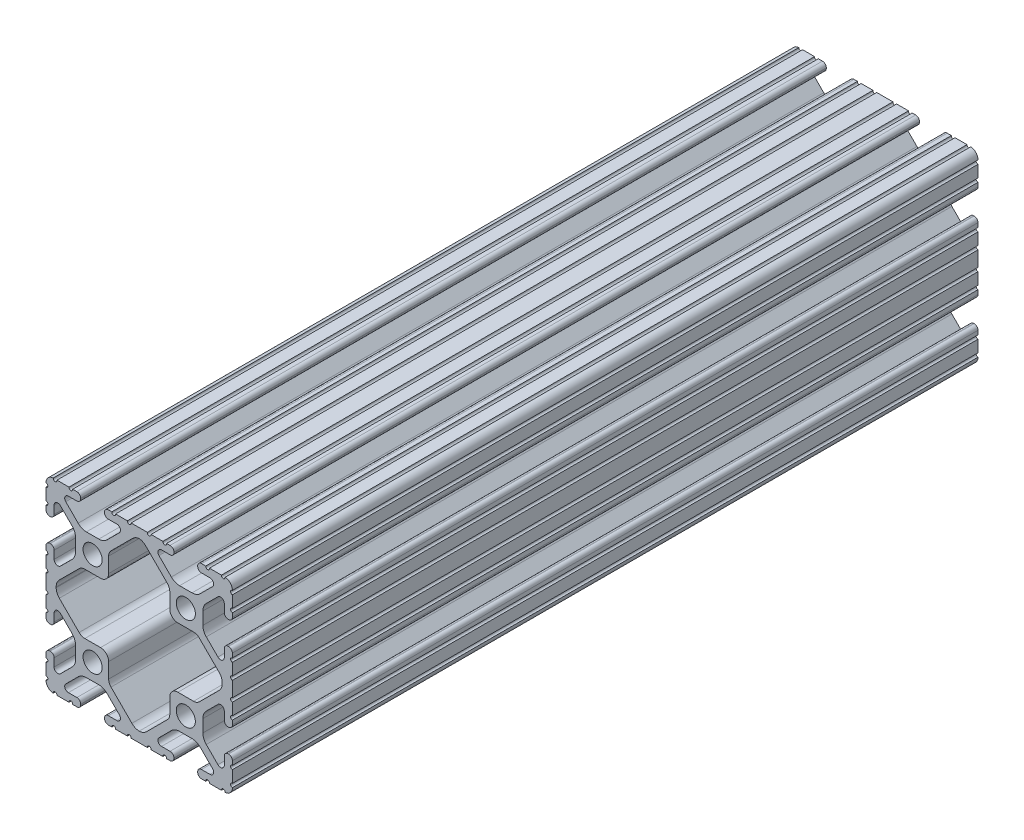
SolidWorks part; units mm, degrees
material "6061-T6 (SS)"
ref_plane "Front Plane" through (0, 0, 0) normal (0, 0, 1) x (1, 0, 0)
ref_plane "Top Plane" through (0, 0, 0) normal (0, 1, 0) x (1, 0, 0)
ref_plane "Right Plane" through (0, 0, 0) normal (1, 0, 0) x (0, 0, -1)
sketch "Sketch1" plane through (0, 0, 0) normal (0, 0, 1) x (1, 0, 0)
  line L0 (-7.684, -16.0797) -> (-1.9878, -21.7759)
  line L1 (-8.3312, -10.3886) -> (-8.3312, -14.5171)
  line L2 (-14.8165, -8.1788) -> (-10.541, -8.1788)
  line L3 (-21.7734, -2.1502) -> (-16.3772, -7.5334)
  line L4 (-22.6314, 0.0822) -> (-22.6314, -0.0822)
  line L5 (-16.3772, 7.5334) -> (-21.7734, 2.1502)
  line L6 (-10.541, 8.1788) -> (-14.8165, 8.1788)
  line L7 (-8.3312, 14.5171) -> (-8.3312, 10.3886)
  line L8 (-1.7956, 21.9681) -> (-7.684, 16.0797)
  line L9 (7.684, 16.0797) -> (1.7956, 21.9681)
  line L10 (8.3312, 10.389) -> (8.3312, 14.5171)
  line L11 (14.8161, 8.1792) -> (10.541, 8.1792)
  line L12 (21.7734, 2.1502) -> (16.3768, 7.5339)
  line L13 (22.6314, -0.0822) -> (22.6314, 0.0822)
  line L14 (16.3772, -7.5334) -> (21.7734, -2.1502)
  line L15 (10.541, -8.1788) -> (14.8165, -8.1788)
  line L16 (8.3312, -14.5171) -> (8.3312, -10.3886)
  line L17 (1.9878, -21.7759) -> (7.684, -16.0797)
  line L18 (7.4579, -25.4) -> (8.4051, -25.4)
  line L19 (9.4615, -24.3587) -> (9.4615, -24.2315)
  line L20 (8.4051, -23.1902) -> (6.0878, -23.1902)
  line L21 (5.388, -21.5008) -> (8.763, -18.1257)
  line L22 (11.0081, -17.1958) -> (14.3919, -17.1958)
  line L23 (16.637, -18.1257) -> (20.012, -21.5008)
  line L24 (19.2977, -23.1901) -> (16.9799, -23.1901)
  line L25 (15.9385, -24.2315) -> (15.9385, -24.3587)
  line L26 (16.9949, -25.4) -> (18.134, -25.4)
  line L27 (19.1384, -25.4) -> (22.4132, -25.4)
  line L28 (23.4176, -25.4) -> (23.4501, -25.4)
  line L29 (25.4, -23.2977) -> (25.4, -23.2686)
  line L30 (25.4, -22.2526) -> (25.4, -19.0252)
  line L31 (25.4, -18.0092) -> (25.4, -16.916)
  line L32 (24.3586, -15.8746) -> (24.2316, -15.8746)
  line L33 (23.1902, -16.916) -> (23.1902, -19.101)
  line L34 (21.4558, -19.8194) -> (18.2781, -16.6418)
  line L35 (17.3482, -14.3967) -> (17.3482, -11.0035)
  line L36 (18.2808, -8.7557) -> (21.4566, -5.5875)
  line L37 (23.1902, -6.3068) -> (23.1902, -8.484)
  line L38 (24.2316, -9.5254) -> (24.3586, -9.5254)
  line L39 (25.4, -8.484) -> (25.4, -7.3277)
  line L40 (25.4, -6.3117) -> (25.4, -3.0843)
  line L41 (25.4, -2.0683) -> (25.4, 2.0683)
  line L42 (25.4, 3.0843) -> (25.4, 6.3117)
  line L43 (25.4, 7.3277) -> (25.4, 8.484)
  line L44 (24.3586, 9.5254) -> (24.2316, 9.5254)
  line L45 (23.1902, 8.484) -> (23.1902, 6.3068)
  line L46 (21.4566, 5.5875) -> (18.2808, 8.7557)
  line L47 (17.3482, 11.0035) -> (17.3482, 14.3967)
  line L48 (18.2781, 16.6418) -> (21.4558, 19.8194)
  line L49 (23.1902, 19.101) -> (23.1902, 16.916)
  line L50 (24.2316, 15.8746) -> (24.3586, 15.8746)
  line L51 (25.4, 16.916) -> (25.4, 18.0092)
  line L52 (25.4, 19.0252) -> (25.4, 22.2526)
  line L53 (25.4, 23.2686) -> (25.4, 23.2977)
  line L54 (23.4501, 25.4) -> (23.4176, 25.4)
  line L55 (22.4132, 25.4) -> (19.1384, 25.4)
  line L56 (18.134, 25.4) -> (16.9949, 25.4)
  line L57 (15.9385, 24.3587) -> (15.9385, 24.2315)
  line L58 (16.9799, 23.1901) -> (19.2977, 23.1901)
  line L59 (20.012, 21.5008) -> (16.637, 18.1257)
  line L60 (14.3919, 17.1958) -> (11.0081, 17.1958)
  line L61 (8.763, 18.1257) -> (5.388, 21.5008)
  line L62 (6.0878, 23.1902) -> (8.4051, 23.1902)
  line L63 (9.4615, 24.2315) -> (9.4615, 24.3587)
  line L64 (8.4051, 25.4) -> (7.4579, 25.4)
  line L65 (6.4535, 25.4) -> (3.2145, 25.4)
  line L66 (2.2101, 25.4) -> (-2.2101, 25.4)
  line L67 (-3.2145, 25.4) -> (-6.4535, 25.4)
  line L68 (-7.4579, 25.4) -> (-8.4051, 25.4)
  line L69 (-9.4615, 24.3587) -> (-9.4615, 24.2315)
  line L70 (-8.4051, 23.1902) -> (-6.0878, 23.1902)
  line L71 (-5.388, 21.5008) -> (-8.763, 18.1257)
  line L72 (-11.0081, 17.1958) -> (-14.3919, 17.1958)
  line L73 (-16.637, 18.1257) -> (-20.012, 21.5008)
  line L74 (-19.2977, 23.1901) -> (-16.9799, 23.1901)
  line L75 (-15.9385, 24.2315) -> (-15.9385, 24.3587)
  line L76 (-16.9949, 25.4) -> (-18.134, 25.4)
  line L77 (-19.1384, 25.4) -> (-22.4132, 25.4)
  line L78 (-23.4176, 25.4) -> (-23.4501, 25.4)
  line L79 (-25.4, 23.2977) -> (-25.4, 23.2686)
  line L80 (-25.4, 22.2526) -> (-25.4, 19.0252)
  line L81 (-25.4, 18.0092) -> (-25.4, 16.916)
  line L82 (-24.3586, 15.8746) -> (-24.2316, 15.8746)
  line L83 (-23.1902, 16.916) -> (-23.1902, 19.101)
  line L84 (-21.4558, 19.8194) -> (-18.2781, 16.6418)
  line L85 (-17.3482, 14.3967) -> (-17.3482, 11.0035)
  line L86 (-18.2808, 8.7557) -> (-21.4566, 5.5875)
  line L87 (-23.1902, 6.3068) -> (-23.1902, 8.484)
  line L88 (-24.2316, 9.5254) -> (-24.3586, 9.5254)
  line L89 (-25.4, 8.484) -> (-25.4, 7.3277)
  line L90 (-25.4, 6.3117) -> (-25.4, 3.0843)
  line L91 (-25.4, 2.0683) -> (-25.4, -2.0683)
  line L92 (-25.4, -3.0843) -> (-25.4, -6.3117)
  line L93 (-25.4, -7.3277) -> (-25.4, -8.484)
  line L94 (-24.3586, -9.5254) -> (-24.2316, -9.5254)
  line L95 (-23.1902, -8.484) -> (-23.1902, -6.3068)
  line L96 (-21.4566, -5.5875) -> (-18.2808, -8.7557)
  line L97 (-17.3482, -11.0035) -> (-17.3482, -14.3967)
  line L98 (-18.2781, -16.6418) -> (-21.4558, -19.8194)
  line L99 (-23.1902, -19.101) -> (-23.1902, -16.916)
  line L100 (-24.2316, -15.8746) -> (-24.3586, -15.8746)
  line L101 (-25.4, -16.916) -> (-25.4, -18.0092)
  line L102 (-25.4, -19.0252) -> (-25.4, -22.2526)
  line L103 (-25.4, -23.2686) -> (-25.4, -23.2977)
  line L104 (-23.4501, -25.4) -> (-23.4176, -25.4)
  line L105 (-22.4132, -25.4) -> (-19.1384, -25.4)
  line L106 (-18.134, -25.4) -> (-16.9949, -25.4)
  line L107 (-15.9385, -24.3587) -> (-15.9385, -24.2315)
  line L108 (-16.9799, -23.1901) -> (-19.2977, -23.1901)
  line L109 (-20.012, -21.5008) -> (-16.637, -18.1257)
  line L110 (-14.3919, -17.1958) -> (-11.0081, -17.1958)
  line L111 (-8.763, -18.1257) -> (-5.388, -21.5008)
  line L112 (-6.0878, -23.1902) -> (-8.4051, -23.1902)
  line L113 (-9.4615, -24.2315) -> (-9.4615, -24.3587)
  line L114 (-8.4051, -25.4) -> (-7.4579, -25.4)
  line L115 (-6.4535, -25.4) -> (-3.2145, -25.4)
  line L116 (-2.2101, -25.4) -> (2.2101, -25.4)
  line L117 (3.2145, -25.4) -> (6.4535, -25.4)
  circle A0 centre (-12.7, 12.7) radius 2.6035
  circle A1 centre (12.7, 12.7) radius 2.6035
  circle A2 centre (12.7, -12.7) radius 2.6035
  circle A3 centre (-12.7, -12.7) radius 2.6035
  arc A4 (-1.9878, -21.7759) -> (0, -22.6304) centre (0.0777, -19.7104) ccw
  arc A5 (-8.3312, -14.5171) -> (-7.684, -16.0797) centre (-6.1214, -14.5171) ccw
  arc A6 (-8.3312, -10.3886) -> (-10.541, -8.1788) centre (-10.541, -10.3886) ccw
  arc A7 (-16.3772, -7.5334) -> (-14.8165, -8.1788) centre (-14.8165, -5.969) ccw
  arc A8 (-22.6314, -0.0822) -> (-21.7734, -2.1502) centre (-19.7104, -0.0822) ccw
  arc A9 (-21.7734, 2.1502) -> (-22.6314, 0.0822) centre (-19.7104, 0.0822) ccw
  arc A10 (-14.8165, 8.1788) -> (-16.3772, 7.5334) centre (-14.8165, 5.969) ccw
  arc A11 (-10.541, 8.1788) -> (-8.3312, 10.3886) centre (-10.541, 10.3886) ccw
  arc A12 (-7.684, 16.0797) -> (-8.3312, 14.5171) centre (-6.1214, 14.5171) ccw
  arc A13 (0, 22.8111) -> (-1.7956, 21.9681) centre (0.2699, 19.9026) ccw
  arc A14 (1.7956, 21.9681) -> (0, 22.8111) centre (-0.2699, 19.9026) ccw
  arc A15 (8.3312, 14.5171) -> (7.684, 16.0797) centre (6.1214, 14.5171) ccw
  arc A16 (8.3312, 10.389) -> (10.541, 8.1792) centre (10.541, 10.389) ccw
  arc A17 (16.3768, 7.5339) -> (14.8161, 8.1792) centre (14.8161, 5.9694) ccw
  arc A18 (22.6314, 0.0822) -> (21.7734, 2.1502) centre (19.7104, 0.0822) ccw
  arc A19 (21.7734, -2.1502) -> (22.6314, -0.0822) centre (19.7104, -0.0822) ccw
  arc A20 (14.8165, -8.1788) -> (16.3772, -7.5334) centre (14.8165, -5.969) ccw
  arc A21 (10.541, -8.1788) -> (8.3312, -10.3886) centre (10.541, -10.3886) ccw
  arc A22 (7.684, -16.0797) -> (8.3312, -14.5171) centre (6.1214, -14.5171) ccw
  arc A23 (0, -22.6304) -> (1.9878, -21.7759) centre (-0.0777, -19.7104) ccw
  arc A24 (7.4579, -25.4) -> (6.4535, -25.4) centre (6.9557, -25.3234) ccw
  arc A25 (8.4051, -25.4) -> (9.4615, -24.3587) centre (8.4201, -24.3587) ccw
  arc A26 (9.4615, -24.2315) -> (8.4051, -23.1902) centre (8.4201, -24.2315) ccw
  arc A27 (5.388, -21.5008) -> (6.0878, -23.1902) centre (6.0878, -22.2006) ccw
  arc A28 (11.0081, -17.1958) -> (8.763, -18.1257) centre (11.0081, -20.3708) ccw
  arc A29 (16.637, -18.1257) -> (14.3919, -17.1958) centre (14.3919, -20.3708) ccw
  arc A30 (19.2977, -23.1901) -> (20.012, -21.5008) centre (19.3122, -22.2006) ccw
  arc A31 (16.9799, -23.1901) -> (15.9385, -24.2315) centre (16.9799, -24.2315) ccw
  arc A32 (15.9385, -24.3587) -> (16.9949, -25.4) centre (16.9799, -24.3587) ccw
  arc A33 (19.1384, -25.4) -> (18.134, -25.4) centre (18.6362, -25.3234) ccw
  arc A34 (23.4176, -25.4) -> (22.4132, -25.4) centre (22.9154, -25.3234) ccw
  arc A35 (23.4501, -25.4) -> (25.4, -23.2977) centre (23.2918, -23.2977) ccw
  arc A36 (25.4, -22.2526) -> (25.4, -23.2686) centre (25.4, -22.7606) ccw
  arc A37 (25.4, -18.0092) -> (25.4, -19.0252) centre (25.4, -18.5172) ccw
  arc A38 (25.4, -16.916) -> (24.3586, -15.8746) centre (24.3586, -16.916) ccw
  arc A39 (24.2316, -15.8746) -> (23.1902, -16.916) centre (24.2316, -16.916) ccw
  arc A40 (21.4558, -19.8194) -> (23.1902, -19.101) centre (22.1742, -19.101) ccw
  arc A41 (17.3482, -14.3967) -> (18.2781, -16.6418) centre (20.5232, -14.3967) ccw
  arc A42 (18.2808, -8.7557) -> (17.3482, -11.0035) centre (20.5232, -11.0035) ccw
  arc A43 (23.1902, -6.3068) -> (21.4566, -5.5875) centre (22.1742, -6.3068) ccw
  arc A44 (23.1902, -8.484) -> (24.2316, -9.5254) centre (24.2316, -8.484) ccw
  arc A45 (24.3586, -9.5254) -> (25.4, -8.484) centre (24.3586, -8.484) ccw
  arc A46 (25.4, -6.3117) -> (25.4, -7.3277) centre (25.4, -6.8197) ccw
  arc A47 (25.4, -2.0683) -> (25.4, -3.0843) centre (25.4, -2.5763) ccw
  arc A48 (25.4, 3.0843) -> (25.4, 2.0683) centre (25.4, 2.5763) ccw
  arc A49 (25.4, 7.3277) -> (25.4, 6.3117) centre (25.4, 6.8197) ccw
  arc A50 (25.4, 8.484) -> (24.3586, 9.5254) centre (24.3586, 8.484) ccw
  arc A51 (24.2316, 9.5254) -> (23.1902, 8.484) centre (24.2316, 8.484) ccw
  arc A52 (21.4566, 5.5875) -> (23.1902, 6.3068) centre (22.1742, 6.3068) ccw
  arc A53 (17.3482, 11.0035) -> (18.2808, 8.7557) centre (20.5232, 11.0035) ccw
  arc A54 (18.2781, 16.6418) -> (17.3482, 14.3967) centre (20.5232, 14.3967) ccw
  arc A55 (23.1902, 19.101) -> (21.4558, 19.8194) centre (22.1742, 19.101) ccw
  arc A56 (23.1902, 16.916) -> (24.2316, 15.8746) centre (24.2316, 16.916) ccw
  arc A57 (24.3586, 15.8746) -> (25.4, 16.916) centre (24.3586, 16.916) ccw
  arc A58 (25.4, 19.0252) -> (25.4, 18.0092) centre (25.4, 18.5172) ccw
  arc A59 (25.4, 23.2686) -> (25.4, 22.2526) centre (25.4, 22.7606) ccw
  arc A60 (25.4, 23.2977) -> (23.4501, 25.4) centre (23.2918, 23.2977) ccw
  arc A61 (22.4132, 25.4) -> (23.4176, 25.4) centre (22.9154, 25.3234) ccw
  arc A62 (18.134, 25.4) -> (19.1384, 25.4) centre (18.6362, 25.3234) ccw
  arc A63 (16.9949, 25.4) -> (15.9385, 24.3587) centre (16.9799, 24.3587) ccw
  arc A64 (15.9385, 24.2315) -> (16.9799, 23.1901) centre (16.9799, 24.2315) ccw
  arc A65 (20.012, 21.5008) -> (19.2977, 23.1901) centre (19.3122, 22.2006) ccw
  arc A66 (14.3919, 17.1958) -> (16.637, 18.1257) centre (14.3919, 20.3708) ccw
  arc A67 (8.763, 18.1257) -> (11.0081, 17.1958) centre (11.0081, 20.3708) ccw
  arc A68 (6.0878, 23.1902) -> (5.388, 21.5008) centre (6.0878, 22.2006) ccw
  arc A69 (8.4051, 23.1902) -> (9.4615, 24.2315) centre (8.4201, 24.2315) ccw
  arc A70 (9.4615, 24.3587) -> (8.4051, 25.4) centre (8.4201, 24.3587) ccw
  arc A71 (6.4535, 25.4) -> (7.4579, 25.4) centre (6.9557, 25.3234) ccw
  arc A72 (2.2101, 25.4) -> (3.2145, 25.4) centre (2.7123, 25.3234) ccw
  arc A73 (-3.2145, 25.4) -> (-2.2101, 25.4) centre (-2.7123, 25.3234) ccw
  arc A74 (-7.4579, 25.4) -> (-6.4535, 25.4) centre (-6.9557, 25.3234) ccw
  arc A75 (-8.4051, 25.4) -> (-9.4615, 24.3587) centre (-8.4201, 24.3587) ccw
  arc A76 (-9.4615, 24.2315) -> (-8.4051, 23.1902) centre (-8.4201, 24.2315) ccw
  arc A77 (-5.388, 21.5008) -> (-6.0878, 23.1902) centre (-6.0878, 22.2006) ccw
  arc A78 (-11.0081, 17.1958) -> (-8.763, 18.1257) centre (-11.0081, 20.3708) ccw
  arc A79 (-16.637, 18.1257) -> (-14.3919, 17.1958) centre (-14.3919, 20.3708) ccw
  arc A80 (-19.2977, 23.1901) -> (-20.012, 21.5008) centre (-19.3122, 22.2006) ccw
  arc A81 (-16.9799, 23.1901) -> (-15.9385, 24.2315) centre (-16.9799, 24.2315) ccw
  arc A82 (-15.9385, 24.3587) -> (-16.9949, 25.4) centre (-16.9799, 24.3587) ccw
  arc A83 (-19.1384, 25.4) -> (-18.134, 25.4) centre (-18.6362, 25.3234) ccw
  arc A84 (-23.4176, 25.4) -> (-22.4132, 25.4) centre (-22.9154, 25.3234) ccw
  arc A85 (-23.4501, 25.4) -> (-25.4, 23.2977) centre (-23.2918, 23.2977) ccw
  arc A86 (-25.4, 22.2526) -> (-25.4, 23.2686) centre (-25.4, 22.7606) ccw
  arc A87 (-25.4, 18.0092) -> (-25.4, 19.0252) centre (-25.4, 18.5172) ccw
  arc A88 (-25.4, 16.916) -> (-24.3586, 15.8746) centre (-24.3586, 16.916) ccw
  arc A89 (-24.2316, 15.8746) -> (-23.1902, 16.916) centre (-24.2316, 16.916) ccw
  arc A90 (-21.4558, 19.8194) -> (-23.1902, 19.101) centre (-22.1742, 19.101) ccw
  arc A91 (-17.3482, 14.3967) -> (-18.2781, 16.6418) centre (-20.5232, 14.3967) ccw
  arc A92 (-18.2808, 8.7557) -> (-17.3482, 11.0035) centre (-20.5232, 11.0035) ccw
  arc A93 (-23.1902, 6.3068) -> (-21.4566, 5.5875) centre (-22.1742, 6.3068) ccw
  arc A94 (-23.1902, 8.484) -> (-24.2316, 9.5254) centre (-24.2316, 8.484) ccw
  arc A95 (-24.3586, 9.5254) -> (-25.4, 8.484) centre (-24.3586, 8.484) ccw
  arc A96 (-25.4, 6.3117) -> (-25.4, 7.3277) centre (-25.4, 6.8197) ccw
  arc A97 (-25.4, 2.0683) -> (-25.4, 3.0843) centre (-25.4, 2.5763) ccw
  arc A98 (-25.4, -3.0843) -> (-25.4, -2.0683) centre (-25.4, -2.5763) ccw
  arc A99 (-25.4, -7.3277) -> (-25.4, -6.3117) centre (-25.4, -6.8197) ccw
  arc A100 (-25.4, -8.484) -> (-24.3586, -9.5254) centre (-24.3586, -8.484) ccw
  arc A101 (-24.2316, -9.5254) -> (-23.1902, -8.484) centre (-24.2316, -8.484) ccw
  arc A102 (-21.4566, -5.5875) -> (-23.1902, -6.3068) centre (-22.1742, -6.3068) ccw
  arc A103 (-17.3482, -11.0035) -> (-18.2808, -8.7557) centre (-20.5232, -11.0035) ccw
  arc A104 (-18.2781, -16.6418) -> (-17.3482, -14.3967) centre (-20.5232, -14.3967) ccw
  arc A105 (-23.1902, -19.101) -> (-21.4558, -19.8194) centre (-22.1742, -19.101) ccw
  arc A106 (-23.1902, -16.916) -> (-24.2316, -15.8746) centre (-24.2316, -16.916) ccw
  arc A107 (-24.3586, -15.8746) -> (-25.4, -16.916) centre (-24.3586, -16.916) ccw
  arc A108 (-25.4, -19.0252) -> (-25.4, -18.0092) centre (-25.4, -18.5172) ccw
  arc A109 (-25.4, -23.2686) -> (-25.4, -22.2526) centre (-25.4, -22.7606) ccw
  arc A110 (-25.4, -23.2977) -> (-23.4501, -25.4) centre (-23.2918, -23.2977) ccw
  arc A111 (-22.4132, -25.4) -> (-23.4176, -25.4) centre (-22.9154, -25.3234) ccw
  arc A112 (-18.134, -25.4) -> (-19.1384, -25.4) centre (-18.6362, -25.3234) ccw
  arc A113 (-16.9949, -25.4) -> (-15.9385, -24.3587) centre (-16.9799, -24.3587) ccw
  arc A114 (-15.9385, -24.2315) -> (-16.9799, -23.1901) centre (-16.9799, -24.2315) ccw
  arc A115 (-20.012, -21.5008) -> (-19.2977, -23.1901) centre (-19.3122, -22.2006) ccw
  arc A116 (-14.3919, -17.1958) -> (-16.637, -18.1257) centre (-14.3919, -20.3708) ccw
  arc A117 (-8.763, -18.1257) -> (-11.0081, -17.1958) centre (-11.0081, -20.3708) ccw
  arc A118 (-6.0878, -23.1902) -> (-5.388, -21.5008) centre (-6.0878, -22.2006) ccw
  arc A119 (-8.4051, -23.1902) -> (-9.4615, -24.2315) centre (-8.4201, -24.2315) ccw
  arc A120 (-9.4615, -24.3587) -> (-8.4051, -25.4) centre (-8.4201, -24.3587) ccw
  arc A121 (-6.4535, -25.4) -> (-7.4579, -25.4) centre (-6.9557, -25.3234) ccw
  arc A122 (-2.2101, -25.4) -> (-3.2145, -25.4) centre (-2.7123, -25.3234) ccw
  arc A123 (3.2145, -25.4) -> (2.2101, -25.4) centre (2.7123, -25.3234) ccw
extrude "Boss-Extrude1" add sketch "Sketch1" along normal mid plane 203.2
